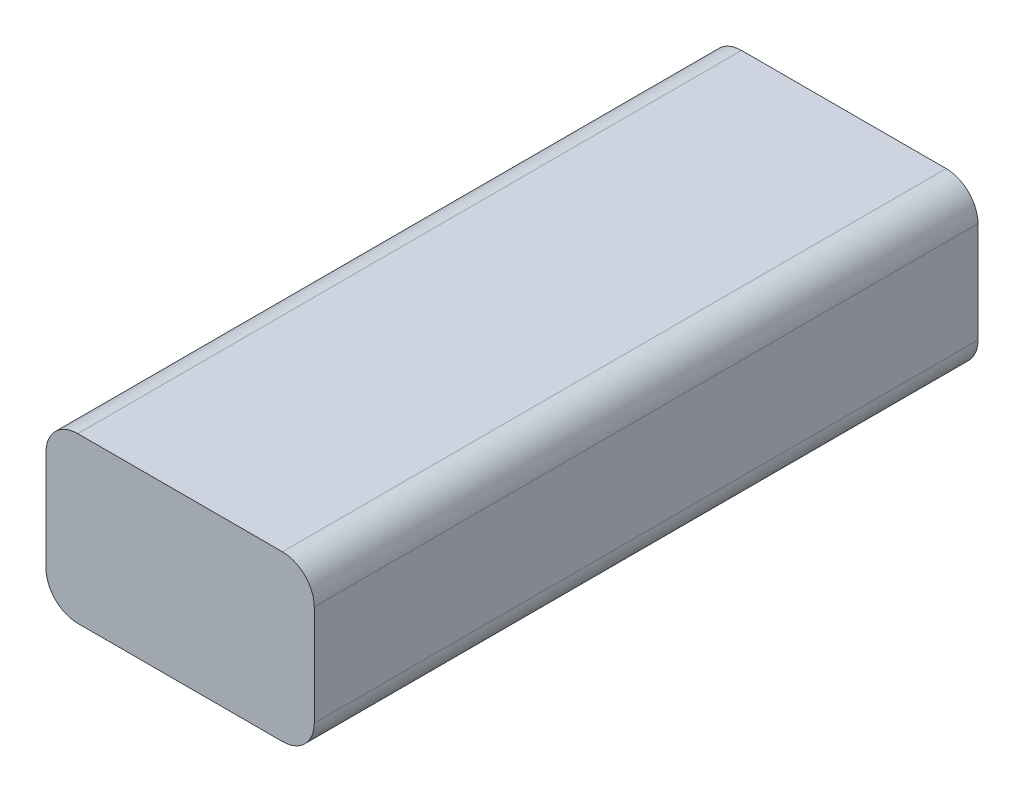
SolidWorks part; units mm, degrees
ref_plane "Front Plane" through (0, 0, 0) normal (0, 0, 1) x (1, 0, 0)
ref_plane "Top Plane" through (0, 0, 0) normal (0, 1, 0) x (1, 0, 0)
ref_plane "Right Plane" through (0, 0, 0) normal (1, 0, 0) x (0, 0, -1)
sketch "Holder Outline" plane through (0, 0, 0) normal (0, 1, 0) x (1, 0, 0)
  line L0 (-12.65, -31.3) -> (12.65, -31.3)
  line L1 (12.65, -31.3) -> (12.65, 31.3)
  line L2 (12.65, 31.3) -> (-12.65, 31.3)
  line L3 (-12.65, 31.3) -> (-12.65, -31.3)
extrude "2xAAA Holder 25.3x62.6x15.5" add sketch "Holder Outline" along normal blind 15.5
fillet "Long Edge Fillets R3" radius 3 4 edges at (-12.65, 0, 0) (12.65, 0, 0) (-12.65, 15.5, 0) (12.65, 15.5, 0)
sketch "Slide Switch Body 7x4" plane through (0, 0, 0) normal (0, 1, 0) x (1, 0, 0)
  line L0 (-3.5, 27.3) -> (3.5, 27.3)
  line L1 (3.5, 27.3) -> (3.5, 23.3)
  line L2 (3.5, 23.3) -> (-3.5, 23.3)
  line L3 (-3.5, 23.3) -> (-3.5, 27.3)
sketch "Slide Switch Lever Sketch" plane through (0, 0, 0) normal (0, 1, 0) x (1, 0, 0)
  line L0 (-1.5, 26.8) -> (1.5, 26.8)
  line L1 (1.5, 26.8) -> (1.5, 23.8)
  line L2 (1.5, 23.8) -> (-1.5, 23.8)
  line L3 (-1.5, 23.8) -> (-1.5, 26.8)
extrude "Slide Switch Lever 3x3x1.3" add sketch "Slide Switch Lever Sketch" against normal blind 1.3
